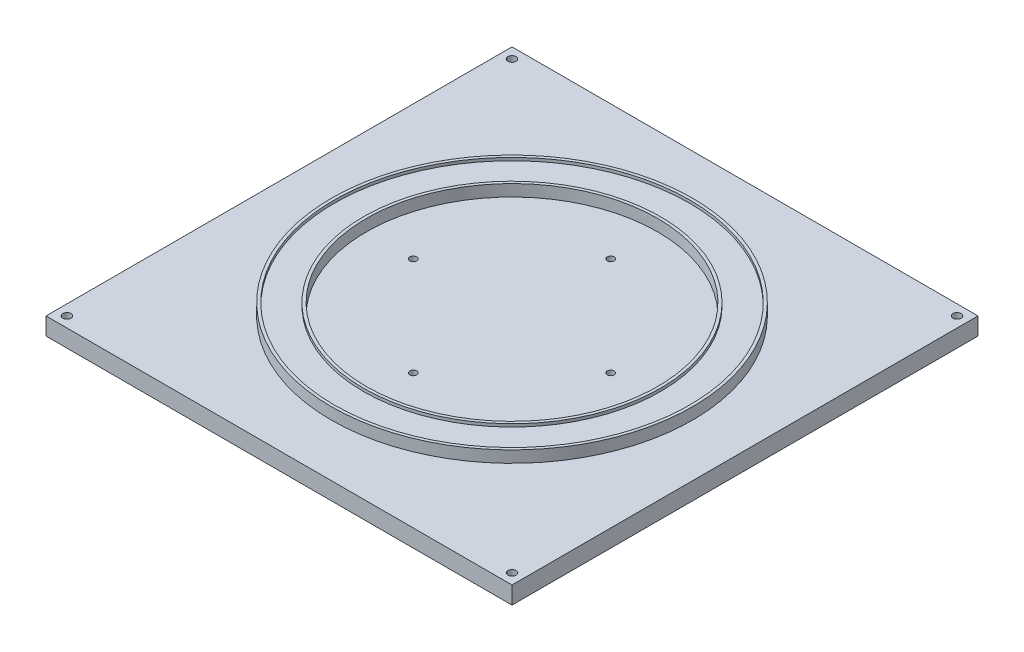
SolidWorks part; units mm, degrees
material "AISI 304"
ref_plane "Front Plane" through (0, 0, 0) normal (0, 0, 1) x (1, 0, 0)
ref_plane "Top Plane" through (0, 0, 0) normal (0, 1, 0) x (1, 0, 0)
ref_plane "Right Plane" through (0, 0, 0) normal (1, 0, 0) x (0, 0, -1)
sketch "Sketch1" plane through (0, 0, 0) normal (0, 1, 0) x (1, 0, 0)
  line L1 (-400, 400) -> (400, 400)
  line L2 (-400, 400) -> (-400, -400)
  line L3 (-400, -400) -> (400, -400)
  line L4 (400, 400) -> (400, -400)
  line L5 (-400, 400) -> (400, -400) construction
  line L6 (-400, -400) -> (400, 400) construction
  point P0 (0, 0)
  dimension "D1" = 800
  dimension "D2" = 800
extrude "Boss-Extrude1" add sketch "Sketch1" along normal mid plane 30
sketch "Sketch3" plane through (0, 15, 0) normal (0, 1, 0) x (1, 0, 0)
  circle A0 centre (0, 0) radius 250
  circle A1 centre (0, 0) radius 310
  dimension "D1" = 620
  dimension "D2" = 500
sketch "Sketch4" plane through (0, 15, 0) normal (0, 1, 0) x (1, 0, 0)
  line L0 (-1000, 0) -> (49000, 0) construction
  line L1 (0, -1000) -> (0, 49000) construction
  circle A0 centre (0, 0) radius 169.5 construction
  circle A1 centre (0, 169.5) radius 6
  circle A2 centre (169.5, 0) radius 6
  circle A3 centre (0, -169.5) radius 6
  circle A4 centre (-169.5, 0) radius 6
  dimension "D1" = 12
  dimension "D2" = 12
  dimension "D3" = 339
extrude "Cut-Extrude3" cut sketch "Sketch4" against normal through all
extrude "Boss-Extrude2" add sketch "Sketch3" along normal blind 20
sketch "Sketch5" plane through (0, 35, 0) normal (0, 1, 0) x (1, 0, 0)
  circle A0 centre (0, 0) radius 255
  circle A1 centre (0, 0) radius 305
  dimension "D1" = 510
  dimension "D2" = 610
extrude "Cut-Extrude4" cut sketch "Sketch5" against normal blind 5
sketch "Sketch6" plane through (0, 15, 0) normal (0, 1, 0) x (1, 0, 0)
  line L0 (400, 400) -> (-400, 400) construction
  line L1 (-400, 400) -> (-400, -400) construction
  line L2 (-1000, 0) -> (49000, 0) construction
  line L3 (0, -1000) -> (0, 49000) construction
  circle A0 centre (-382, 382) radius 7
  circle A1 centre (382, 382) radius 7
  circle A2 centre (382, -382) radius 7
  circle A3 centre (-382, -382) radius 7
  dimension "D1" = 14
  dimension "D2" = 18
  dimension "D3" = 18
extrude "Cut-Extrude5" cut sketch "Sketch6" against normal through all
